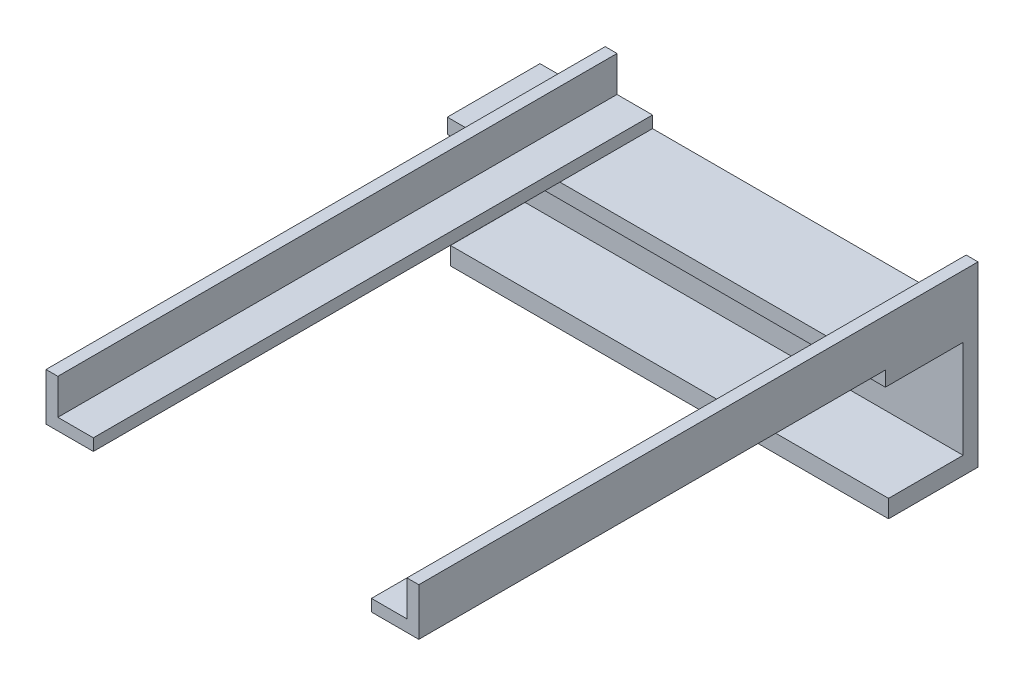
SolidWorks part; units mm, degrees
material "Fundición gris (SN)"
ref_plane "Alzado" through (0, 0, 0) normal (0, 0, 1) x (1, 0, 0)
ref_plane "Planta" through (0, 0, 0) normal (0, 1, 0) x (1, 0, 0)
ref_plane "Vista lateral" through (0, 0, 0) normal (1, 0, 0) x (0, 0, -1)
sketch "Croquis1" plane through (0, 0, 0) normal (0, 0, 1) x (1, 0, 0)
  line L1 (117.5, -35) -> (-117.5, -35)
  line L2 (117.5, -35) -> (117.5, 35)
  line L3 (117.5, 35) -> (-117.5, 35)
  line L4 (-117.5, -35) -> (-117.5, 35)
  line L5 (117.5, -35) -> (-117.5, 35) construction
  line L6 (117.5, 35) -> (-117.5, -35) construction
  point P0 (0, 0)
  dimension "D1" = 235
  dimension "D2" = 70
extrude "Saliente-Extruir1" add sketch "Croquis1" along normal blind 8
sketch "Croquis2" plane through (0, 35, 0) normal (0, 1, 0) x (1, 0, 0)
  line L0 (-117.5, -8) -> (-117.5, 0) construction
  line L1 (117.5, 0) -> (-117.5, 0)
  line L2 (117.5, 0) -> (117.5, -49.6985)
  line L3 (117.5, -49.6985) -> (-117.5, -49.6985)
  line L4 (-117.5, 0) -> (-117.5, -49.6985)
extrude "Saliente-Extruir2" add sketch "Croquis2" against normal blind 8
sketch "Croquis3" plane through (0, 0, 0) normal (0, 0, -1) x (-1, 0, 0)
  line L0 (-117.5, 35) -> (-117.5, 60.4)
  line L1 (-117.5, 60.4) -> (-111.15, 60.4)
  line L2 (-111.15, 60.4) -> (-111.15, 41.35)
  line L3 (-111.15, 41.35) -> (-92.1, 41.35)
  line L4 (-92.1, 41.35) -> (-92.1, 35)
  line L5 (117.5, 35) -> (-117.5, 35) construction
  line L6 (-92.1, 35) -> (-117.5, 35)
  line L8 (57.1, 35) -> (82.5, 35)
  line L9 (57.1, 41.35) -> (57.1, 35)
  line L10 (76.15, 41.35) -> (57.1, 41.35)
  line L11 (76.15, 60.4) -> (76.15, 41.35)
  line L12 (82.5, 60.4) -> (76.15, 60.4)
  line L13 (82.5, 35) -> (82.5, 60.4)
  dimension "D1" = 6.35
  dimension "D2" = 6.35
  dimension "D3" = 25.4
  dimension "D4" = 25.4
  dimension "D5" = 200
extrude "Saliente-Extruir3" add sketch "Croquis3" against normal blind 300
sketch "Croquis4" plane through (0, 0, 8) normal (0, 0, 1) x (1, 0, 0)
  line L0 (117.5, -35) -> (117.5, 27) construction
  line L1 (-117.5, -35) -> (117.5, -35)
  line L2 (-117.5, -35) -> (-117.5, -25.475)
  line L3 (-117.5, -25.475) -> (117.5, -25.475)
  line L4 (117.5, -35) -> (117.5, -25.475)
  dimension "D1" = 9.525
extrude "Saliente-Extruir4" add sketch "Croquis4" along normal blind 40
equation "\"D2@Croquis3\"=\"D1@Croquis3\""
